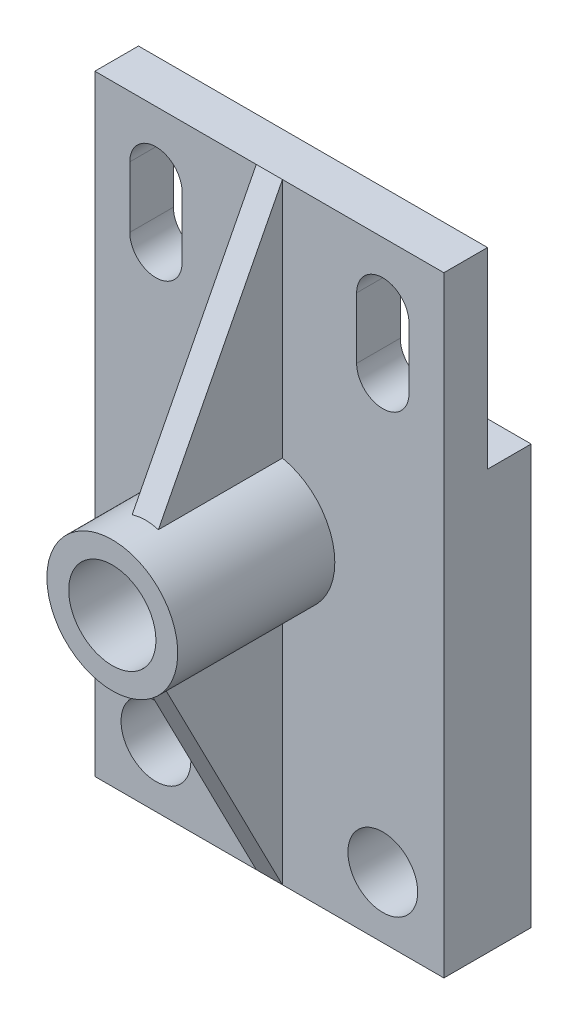
SolidWorks part; units mm, degrees
ref_plane "Спереди" through (0, 0, 0) normal (0, 0, 1) x (1, 0, 0)
ref_plane "Сверху" through (0, 0, 0) normal (0, 1, 0) x (1, 0, 0)
ref_plane "Справа" through (0, 0, 0) normal (1, 0, 0) x (0, 0, -1)
sketch "Эскиз1" plane through (0, 0, 0) normal (0, 0, 1) x (1, 0, 0)
  line L0 (13, 21) -> (13, 28) construction
  line L1 (-20, -35) -> (20, -35)
  line L2 (-20, -35) -> (-20, 35)
  line L3 (-20, 35) -> (20, 35)
  line L4 (20, -35) -> (20, 35)
  line L5 (-20, -35) -> (20, 35) construction
  line L6 (-20, 35) -> (20, -35) construction
  line L7 (10, 21) -> (10, 28)
  line L8 (16, 21) -> (16, 28)
  line L9 (-13, 21) -> (-13, 28) construction
  line L10 (-16, 21) -> (-16, 28)
  line L11 (-10, 21) -> (-10, 28)
  circle A0 centre (13, -28) radius 4
  circle A1 centre (-13, -28) radius 4
  arc A2 (10, 21) -> (16, 21) centre (13, 21) ccw
  arc A3 (16, 28) -> (10, 28) centre (13, 28) ccw
  arc A4 (-16, 21) -> (-10, 21) centre (-13, 21) ccw
  arc A5 (-10, 28) -> (-16, 28) centre (-13, 28) ccw
  point P0 (0, 0)
  point P12 (13, 24.5)
  point P17 (-13, 24.5)
  dimension "D3" = 8
  dimension "D5" = 7
  dimension "D7" = 3
  dimension "D8" = 3
  dimension "D1" = 40
  dimension "D2" = 70
  dimension "D4" = 7
  dimension "D6" = 7
  dimension "D9" = 7
  dimension "D10" = 7
extrude "Бобышка-Вытянуть1" add sketch "Эскиз1" along normal blind 10
sketch "Эскиз2" plane through (20, 0, 0) normal (1, 0, 0) x (0, 0, -1)
  line L1 (0, 35) -> (-5, 35)
  line L2 (0, 35) -> (0, 13)
  line L3 (0, 13) -> (-5, 13)
  line L4 (-5, 35) -> (-5, 13)
  dimension "D1" = 5
  dimension "D2" = 22
extrude "Вырез-Вытянуть1" cut sketch "Эскиз2" against normal through all
sketch "Эскиз3" plane through (0, 0, 10) normal (0, 0, 1) x (1, 0, 0)
  circle A0 centre (0, 0) radius 7.5
  dimension "D1" = 15
extrude "Бобышка-Вытянуть2" add sketch "Эскиз3" along normal blind 18
sketch "Эскиз4" plane through (0, 0, 28) normal (0, 0, 1) x (1, 0, 0)
  circle A0 centre (0, 0) radius 10
  dimension "D1" = 20
extrude "Бобышка-Вытянуть3" add sketch "Эскиз4" against normal blind 2
sketch "Эскиз5" plane through (0, 0, 0) normal (1, 0, 0) x (0, 0, -1)
  line L0 (-28, 0) -> (0, 0) construction
  line L1 (-28, 10) -> (-28, -10) construction
  line L2 (-10, 35) -> (-28, 0)
  line L3 (-28, 0) -> (-10, -35)
  line L4 (-10, 35) -> (-10, -35)
extrude "Бобышка-Вытянуть4" add sketch "Эскиз5" along normal blind 1.5 and the other way blind 1.5
sketch "Эскиз6" plane through (0, 0, 28) normal (0, 0, 1) x (1, 0, 0)
  circle A0 centre (0, 0) radius 5
  dimension "D1" = 10
extrude "Вырез-Вытянуть2" cut sketch "Эскиз6" against normal through all
sketch "Эскиз7" plane through (0, 0, 26) normal (0, 0, -1) x (-1, 0, 0)
  circle A0 centre (0, 0) radius 7.5 construction
  circle A1 centre (0, 0) radius 7.5
  circle A3 centre (0, 0) radius 10
  circle A4 centre (0, 0) radius 10
  dimension "D1" = 0
extrude "Вырез-Вытянуть3" cut sketch "Эскиз7" against normal through all
